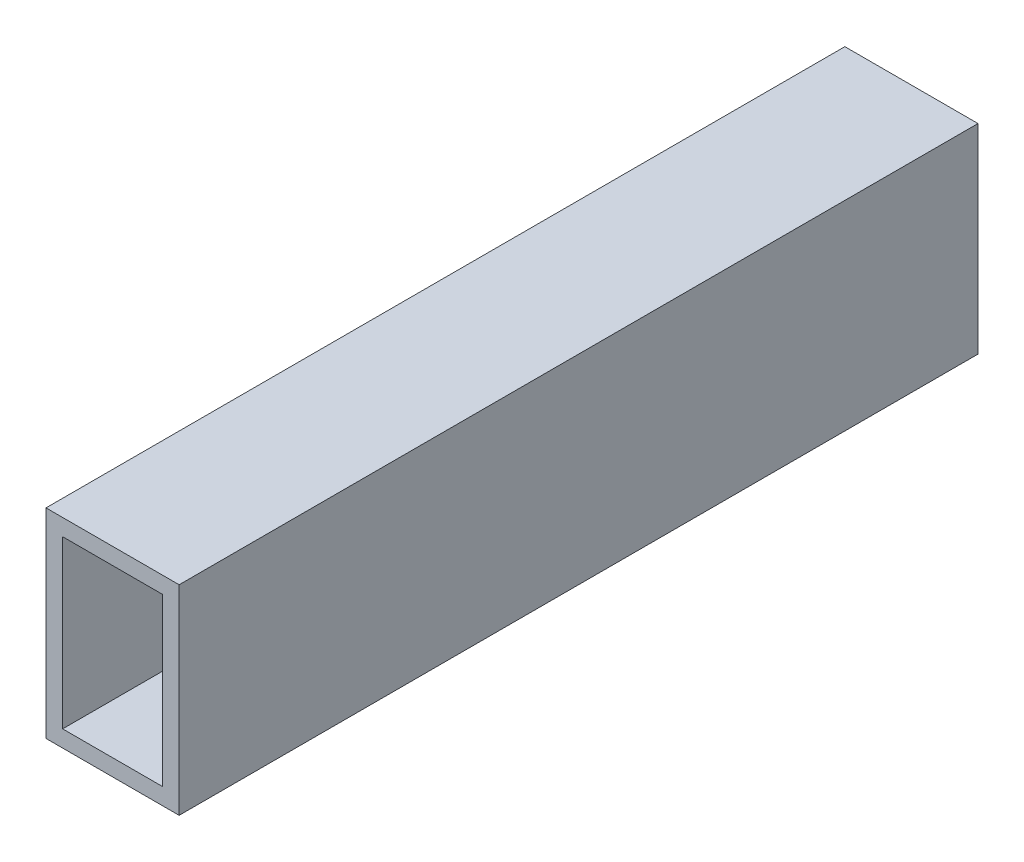
SolidWorks part; units mm, degrees
ref_plane "Front Plane" through (0, 0, 0) normal (0, 0, 1) x (1, 0, 0)
ref_plane "Top Plane" through (0, 0, 0) normal (0, 1, 0) x (1, 0, 0)
ref_plane "Right Plane" through (0, 0, 0) normal (1, 0, 0) x (0, 0, -1)
sketch "Sketch1" plane through (0, 0, 0) normal (0, 0, 1) x (1, 0, 0)
  line L1 (-12.7, 19.05) -> (12.7, 19.05)
  line L2 (-12.7, 19.05) -> (-12.7, -19.05)
  line L3 (-12.7, -19.05) -> (12.7, -19.05)
  line L4 (12.7, 19.05) -> (12.7, -19.05)
  line L5 (-12.7, 19.05) -> (12.7, -19.05) construction
  line L6 (-12.7, -19.05) -> (12.7, 19.05) construction
  line L7 (-9.525, 15.875) -> (9.525, 15.875)
  line L8 (-9.525, 15.875) -> (-9.525, -15.875)
  line L9 (-9.525, -15.875) -> (9.525, -15.875)
  line L10 (9.525, 15.875) -> (9.525, -15.875)
  line L11 (-9.525, 15.875) -> (9.525, -15.875) construction
  line L12 (-9.525, -15.875) -> (9.525, 15.875) construction
  point P0 (0, 0)
  point P6 (0, 0)
  dimension "D1" = 38.1
  dimension "D2" = 25.4
  dimension "D3" = 19.05
  dimension "D4" = 31.75
extrude "Boss-Extrude1" add sketch "Sketch1" along normal blind 152.4
